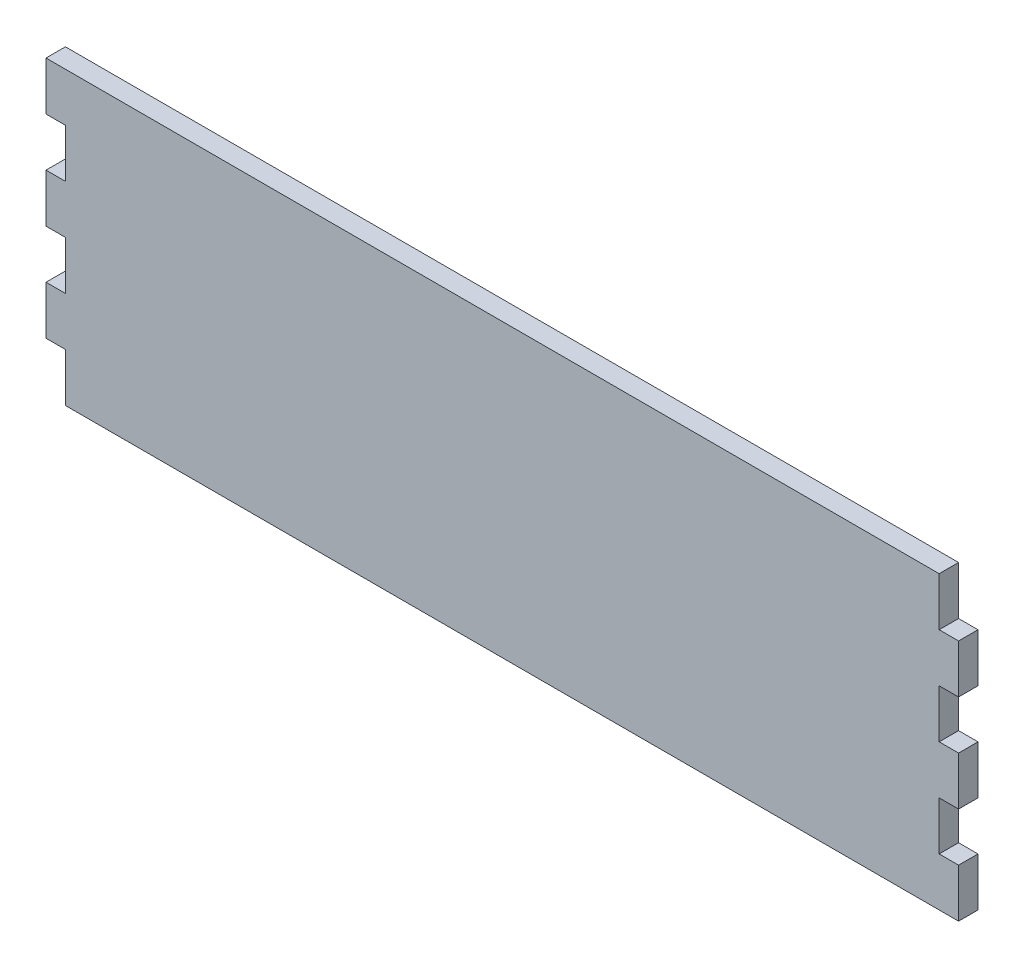
SolidWorks part; units mm, degrees
ref_plane "Спереди" through (0, 0, 0) normal (0, 0, 1) x (1, 0, 0)
ref_plane "Сверху" through (0, 0, 0) normal (0, 1, 0) x (1, 0, 0)
ref_plane "Справа" through (0, 0, 0) normal (1, 0, 0) x (0, 0, -1)
sketch "Эскиз1" plane through (0, 0, 0) normal (0, 0, 1) x (1, 0, 0)
  line L0 (0, 0) -> (0, 12.5)
  line L1 (0, 12.5) -> (-5, 12.5)
  line L2 (-5, 12.5) -> (-5, 25)
  line L3 (-5, 25) -> (0, 25)
  line L4 (0, 25) -> (0, 37.5)
  line L5 (0, 37.5) -> (-5, 37.5)
  line L6 (-5, 37.5) -> (-5, 50)
  line L7 (-5, 50) -> (0, 50)
  line L8 (0, 50) -> (0, 62.5)
  line L9 (0, 62.5) -> (-5, 62.5)
  line L10 (-5, 62.5) -> (-5, 75)
  line L11 (-5, 75) -> (225, 75)
  line L12 (225, 62.5) -> (225, 75)
  line L13 (225, 62.5) -> (230, 62.5)
  line L14 (230, 62.5) -> (230, 50)
  line L15 (230, 50) -> (225, 50)
  line L16 (225, 50) -> (225, 37.5)
  line L17 (225, 37.5) -> (230, 37.5)
  line L18 (230, 37.5) -> (230, 25)
  line L19 (230, 25) -> (225, 25)
  line L20 (225, 25) -> (225, 12.5)
  line L21 (225, 12.5) -> (230, 12.5)
  line L22 (230, 12.5) -> (230, 0)
  line L23 (230, 0) -> (0, 0)
  point P13 (13.0171, -4.7183)
  dimension "D1" = 5
  dimension "D2" = 230
  dimension "D3" = 75
extrude "Бобышка-Вытянуть1" add sketch "Эскиз1" along normal blind 5
